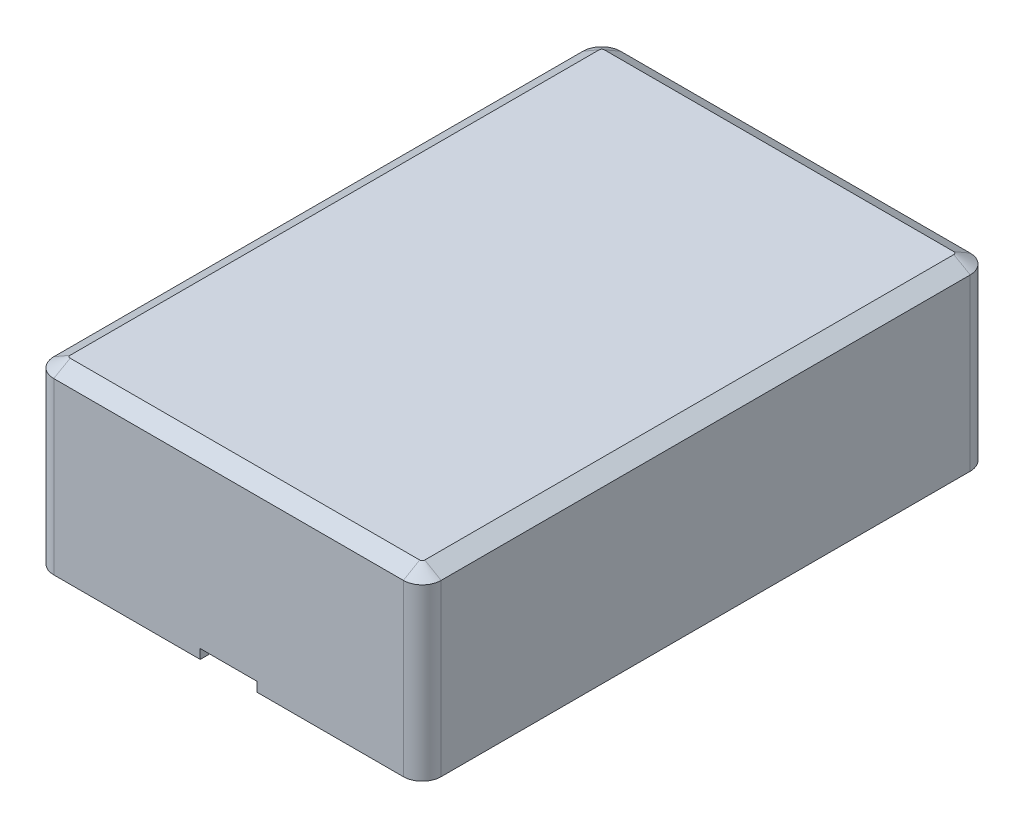
SolidWorks part; units mm, degrees
ref_plane "Спереди" through (0, 0, 0) normal (0, 0, 1) x (1, 0, 0)
ref_plane "Сверху" through (0, 0, 0) normal (0, 1, 0) x (1, 0, 0)
ref_plane "Справа" through (0, 0, 0) normal (1, 0, 0) x (0, 0, -1)
sketch "Эскиз1" plane through (0, 0, 0) normal (0, 1, 0) x (1, 0, 0)
  line L0 (-3.5, 45.8352) -> (-3.5, -34.761) construction
  line L1 (-20.5, -30) -> (20.5, -30)
  line L2 (-20.5, -30) -> (-20.5, 30)
  line L3 (-20.5, 30) -> (20.5, 30)
  line L4 (20.5, -30) -> (20.5, 30)
  line L5 (0, 30) -> (0, -30) construction
  line L6 (-20.5, 0) -> (20.5, 0) construction
  point P0 (0, 0)
  dimension "D3" = 60
  dimension "D5" = 41
  dimension "D8" = 3.5
extrude "Бобышка-Вытянуть1" add sketch "Эскиз1" along normal blind 3
chamfer "Фаска1" [suppressed] distance 2 angle 45
sketch "Эскиз2" plane through (0, 3, 0) normal (0, 1, 0) x (1, 0, 0)
  line L0 (-20.5, 30) -> (20.5, 30)
  line L2 (-20.5, 30) -> (-20.5, -30)
  line L3 (-20.5, -30) -> (20.5, -30)
  line L4 (20.5, 30) -> (20.5, -30)
extrude "Вытянуть-Тонкостенный1" add sketch "Эскиз2" along normal blind 17 thin
sketch "Эскиз3" plane through (0, 20, 0) normal (0, 1, 0) x (1, 0, 0)
  line L0 (0, 32.0771) -> (0, 0) construction
  line L2 (-13.5, 27.9629) -> (13.5, 27.9629)
  line L3 (-13.5, 27.9629) -> (-13.5, 30.9933)
  line L4 (-13.5, 30.9933) -> (13.5, 30.9933)
  line L5 (13.5, 27.9629) -> (13.5, 30.9933)
  line L6 (0, 30.9933) -> (0, 27.9629) construction
  line L7 (-13.5, 29.4781) -> (13.5, 29.4781) construction
  point P3 (0, 29.4781)
  dimension "D1" = 27
extrude "Вырез-Вытянуть1" cut sketch "Эскиз3" against normal up to surface (17 mm away) up to face at (0, 3, 0)
sketch "Эскиз4" plane through (0, 3, 0) normal (0, 1, 0) x (1, 0, 0)
  line L0 (0, 32.478) -> (0, 0) construction
  line L1 (0, 0) -> (39.8357, 0) construction
  line L3 (20.5, -30) -> (20.5, 30) construction
  circle A0 centre (17, 25) radius 2.5
  circle A1 centre (-17, 25) radius 2.5
  circle A2 centre (17, -25) radius 2.5
  circle A3 centre (-17, -25) radius 2.5
  dimension "D1" = 5
  dimension "D3" = 3.5
  dimension "D4" = 50
  dimension "D2" = 25
extrude "Бобышка-Вытянуть2" add sketch "Эскиз4" along normal up to surface (17 mm away) up to face at (0, 20, -9.75)
sketch "Эскиз5" plane through (0, 20, 0) normal (0, 1, 0) x (1, 0, 0)
  line L0 (20.5, -30) -> (20.5, 30) construction
  circle A0 centre (17, 25) radius 1.5
  circle A1 centre (17, -25) radius 1.5
  circle A2 centre (-17, -25) radius 1.5
  circle A3 centre (-17, 25) radius 1.5
  dimension "D1" = 3
  dimension "D2" = 3.5
extrude "Вырез-Вытянуть2" cut sketch "Эскиз5" against normal through all both and the other way through all
sketch "Эскиз8" plane through (0, 3, 0) normal (0, 1, 0) x (1, 0, 0)
  line L0 (-24.1981, 0) -> (27.887, 0) construction
  line L1 (19, -23.5) -> (19, 23.5) construction
  line L2 (19, -11.5) -> (15, -11.5)
  line L3 (19, -11.5) -> (19, -16.5)
  line L4 (19, -16.5) -> (15, -16.5)
  line L5 (15, -11.5) -> (15, -16.5)
  line L6 (-19, 23.5) -> (-19, -23.5) construction
  line L7 (-19, -3) -> (-15, -3)
  line L8 (-19, -3) -> (-19, -8)
  line L9 (-19, -8) -> (-15, -8)
  line L10 (-15, -3) -> (-15, -8)
  dimension "D1" = 11.5
  dimension "D2" = 4
  dimension "D3" = 5
  dimension "D4" = 3
  dimension "D5" = 5
  dimension "D6" = 4
extrude "Бобышка-Вытянуть3" [suppressed] add sketch "Эскиз8" along normal up to surface (18 mm away)
sketch "Эскиз9" plane through (0, 0, -30) normal (0, 0, -1) x (-1, 0, 0)
  line L0 (-20.5, 20) -> (-20.5, 0) construction
  line L1 (-20.5, 3) -> (20.5, 3)
  line L2 (-20.5, 3) -> (-20.5, 0)
  line L3 (-20.5, 0) -> (20.5, 0)
  line L4 (20.5, 3) -> (20.5, 0)
extrude "Вырез-Вытянуть3" cut sketch "Эскиз9" against normal through all
sketch "Эскиз10" plane through (0, 20, 0) normal (0, 1, 0) x (1, 0, 0)
  line L1 (-20.5, 30) -> (20.5, 30)
  line L2 (-20.5, 30) -> (-20.5, -30)
  line L3 (-20.5, -30) -> (20.5, -30)
  line L4 (20.5, 30) -> (20.5, -30)
extrude "Бобышка-Вытянуть4" add sketch "Эскиз10" along normal blind 2
sketch "Эскиз11" plane through (0, 3, 0) normal (0, -1, 0) x (1, 0, 0)
  line L0 (0, 0) -> (0, 58.4661) construction
  line L1 (-3, 27.8468) -> (3, 27.8468)
  line L2 (-3, 27.8468) -> (-3, 30.8599)
  line L3 (-3, 30.8599) -> (3, 30.8599)
  line L4 (3, 27.8468) -> (3, 30.8599)
  line L5 (0, 30.8599) -> (0, 27.8468) construction
  line L6 (-3, 29.3533) -> (3, 29.3533) construction
  point P0 (0, 29.3533)
  point P6 (0, 0)
  dimension "D1" = 6
extrude "Вырез-Вытянуть4" cut sketch "Эскиз11" against normal blind 1
sketch "Эскиз12" plane through (0, 20, 0) normal (0, -1, 0) x (1, 0, 0)
  line L0 (19, 23.5) -> (19, -23.5) construction
  line L1 (19, 23.5) -> (5, 23.5)
  line L2 (19, 23.5) -> (19, 17.5)
  line L3 (19, 17.5) -> (5, 17.5)
  line L4 (5, 23.5) -> (5, 17.5)
  arc A0 (19, -23.5) -> (19, -26.5) centre (17, -25) ccw construction
  point P9 (19, 23.5)
  point P11 (-19, 18)
  dimension "D1" = 42.5
  dimension "D2" = 14
extrude "Бобышка-Вытянуть6" add sketch "Эскиз12" along normal blind 5
fillet "Скругление2" radius 1 2 edges at (12, 15, 17.5) (5, 17.5, 17.5)
fillet "Скругление3" radius 1 1 edges at (0, 4, 28.5)
fillet "Скругление4" radius 2 4 edges at (20.5, 12.5, 30) (20.5, 12.5, -30) (-20.5, 12.5, -30) (-20.5, 12.5, 30)
chamfer "Фаска2" distance 1 angle 60 8 edges at (-19.9142, 22, 29.4142) (-20.5, 22, 0) (-19.9142, 22, -29.4142) (0, 22, -30) (19.9142, 22, -29.4142) (20.5, 22, 0) (19.9142, 22, 29.4142) (0, 22, 30)
